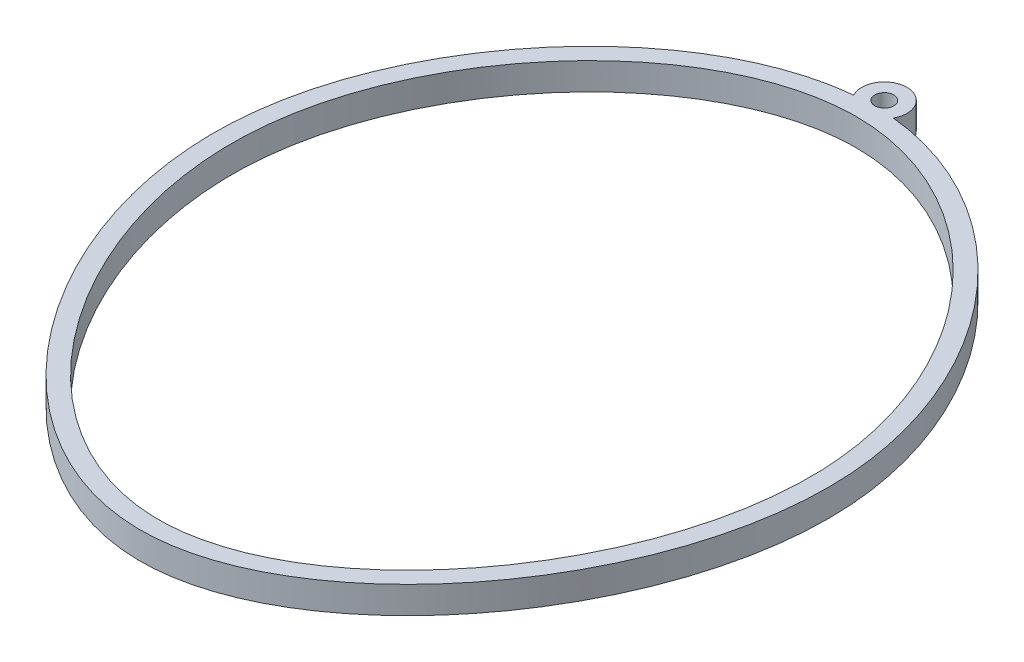
SolidWorks part; units mm, degrees
ref_plane "Front Plane" through (0, 0, 0) normal (0, 0, 1) x (1, 0, 0)
ref_plane "Top Plane" through (0, 0, 0) normal (0, 1, 0) x (1, 0, 0)
ref_plane "Right Plane" through (0, 0, 0) normal (1, 0, 0) x (0, 0, -1)
sketch "Sketch1" plane through (0, 0, 0) normal (0, 1, 0) x (1, 0, 0)
  line L0 (0, 34.7441) -> (0, -42.465) construction
  line L1 (-31.905, 0) -> (31.905, 0) construction
  line L2 (0, 36.7441) -> (0, -44.465) construction
  line L3 (-33.905, 0) -> (33.905, 0) construction
  circle A0 centre (0, 37.844) radius 1.05
  arc A1 (2.1908, 36.6397) -> (-2.1908, 36.6397) centre (0, 37.844) ccw
  spline S0 degree 3 poles (-48.0075, -0.7049) (0, 51.4179) (48.0075, -0.7049) (0, -64.5826) (-48.0075, -0.7049) (0, 51.4179) (48.0075, -0.7049) knots -0.764818 -0.5 -0.235182 0 0.235182 0.5 0.764818 1 1.235182 1.5 1.764818 only from (0, 34.7441) to (0, 34.7441)
  spline S1 degree 3 poles (-50.9992, -0.6687) (0, 54.4049) (50.9992, -0.6687) (0, -67.5871) (-50.9992, -0.6687) (0, 54.4049) (50.9992, -0.6687) knots -0.763974 -0.5 -0.236026 0 0.236026 0.5 0.763974 1 1.236026 1.5 1.763974 only from (0, 36.7441) to (0, 36.7441)
  dimension "D9" = 5
  dimension "D10" = 2.1
  dimension "D1" = 77.209
  dimension "D2" = 63.81
  dimension "D3" = 34.7441
  dimension "D4" = 31.905
  dimension "D5" = 81.209
  dimension "D6" = 2
  dimension "D7" = 67.81
  dimension "D8" = 2
  dimension "D11" = 3.1
extrude "Boss-Extrude1" add sketch "Sketch1" along normal blind 3 contours A1 S1 A0 | S1 S0
equation "\"D7@Sketch1\"=\"D2@Sketch1\"+4"
equation "\"D5@Sketch1\"=\"D1@Sketch1\"+4"
equation "\"D3@Sketch1\"=\"D1@Sketch1\"*0.45"
equation "\"D4@Sketch1\"=\"D2@Sketch1\"*0.5"
